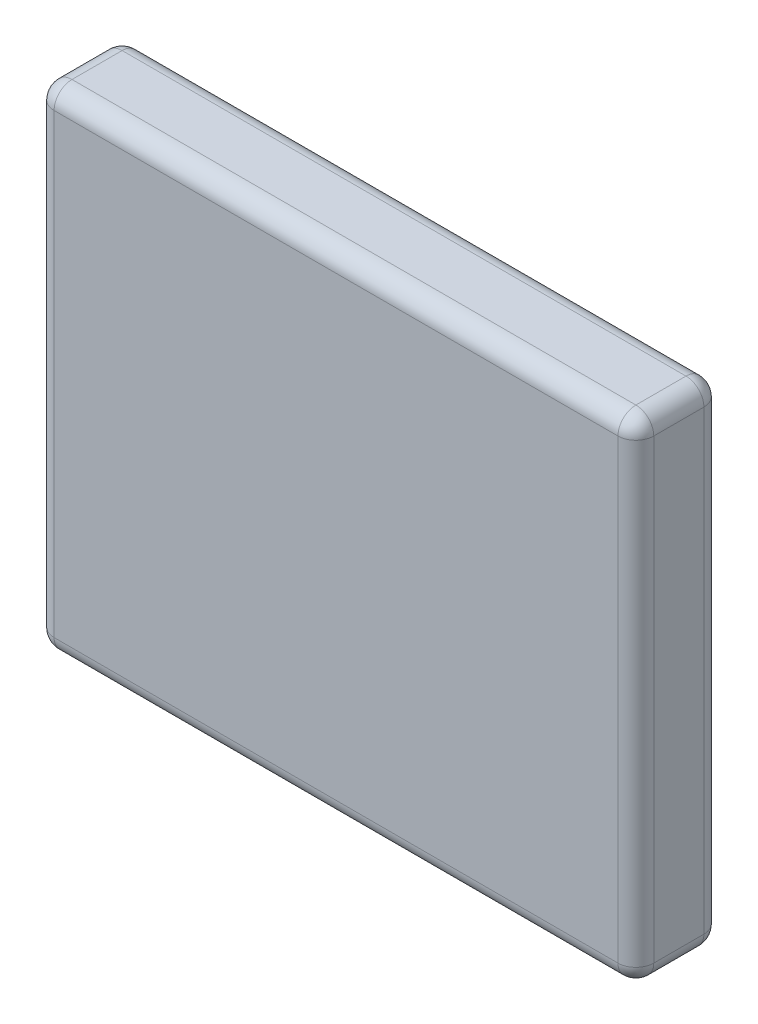
SolidWorks part; units mm, degrees
ref_plane "Front Plane" through (0, 0, 0) normal (0, 0, 1) x (1, 0, 0)
ref_plane "Top Plane" through (0, 0, 0) normal (0, 1, 0) x (1, 0, 0)
ref_plane "Right Plane" through (0, 0, 0) normal (1, 0, 0) x (0, 0, -1)
sketch "Sketch1" plane through (0, 0, 0) normal (0, 0, 1) x (1, 0, 0)
  line L1 (-33.5, 27.5) -> (33.5, 27.5)
  line L2 (-33.5, 27.5) -> (-33.5, -27.5)
  line L3 (-33.5, -27.5) -> (33.5, -27.5)
  line L4 (33.5, 27.5) -> (33.5, -27.5)
  line L5 (-33.5, 27.5) -> (33.5, -27.5) construction
  line L6 (-33.5, -27.5) -> (33.5, 27.5) construction
  point P0 (0, 0)
  dimension "D1" = 55
  dimension "D2" = 67
extrude "Boss-Extrude1" add sketch "Sketch1" along normal blind 9.6
fillet "Fillet1" radius 2 12 edges at (0, 27.5, 0) (-33.5, 0, 0) (0, -27.5, 0) (33.5, 0, 0) (0, -27.5, 9.6) (-33.5, 0, 9.6) (0, 27.5, 9.6) (33.5, 0, 9.6) (-33.5, 27.5, 4.8) (-33.5, -27.5, 4.8) (33.5, -27.5, 4.8) (33.5, 27.5, 4.8)
